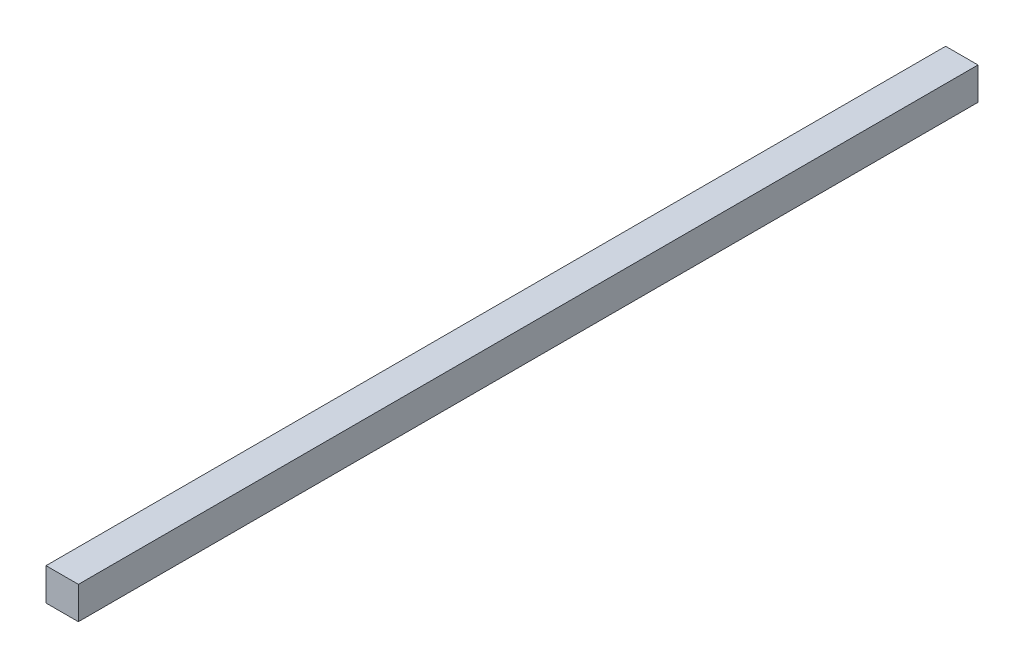
SolidWorks part; units mm, degrees
ref_plane "Front Plane" through (0, 0, 0) normal (0, 0, 1) x (1, 0, 0)
ref_plane "Top Plane" through (0, 0, 0) normal (0, 1, 0) x (1, 0, 0)
ref_plane "Right Plane" through (0, 0, 0) normal (1, 0, 0) x (0, 0, -1)
sketch "Sketch1" plane through (0, 0, 0) normal (0, 0, 1) x (1, 0, 0)
  line L1 (-71, -9) -> (-89, -9)
  line L2 (-71, -9) -> (-71, 9)
  line L3 (-71, 9) -> (-89, 9)
  line L4 (-89, -9) -> (-89, 9)
  line L5 (-71, -9) -> (-89, 9) construction
  line L6 (-71, 9) -> (-89, -9) construction
  point P0 (-80, 0)
  dimension "D1" = 18
  dimension "D2" = 18
extrude "Boss-Extrude1" add sketch "Sketch1" along normal up to vertex (500 mm away)
